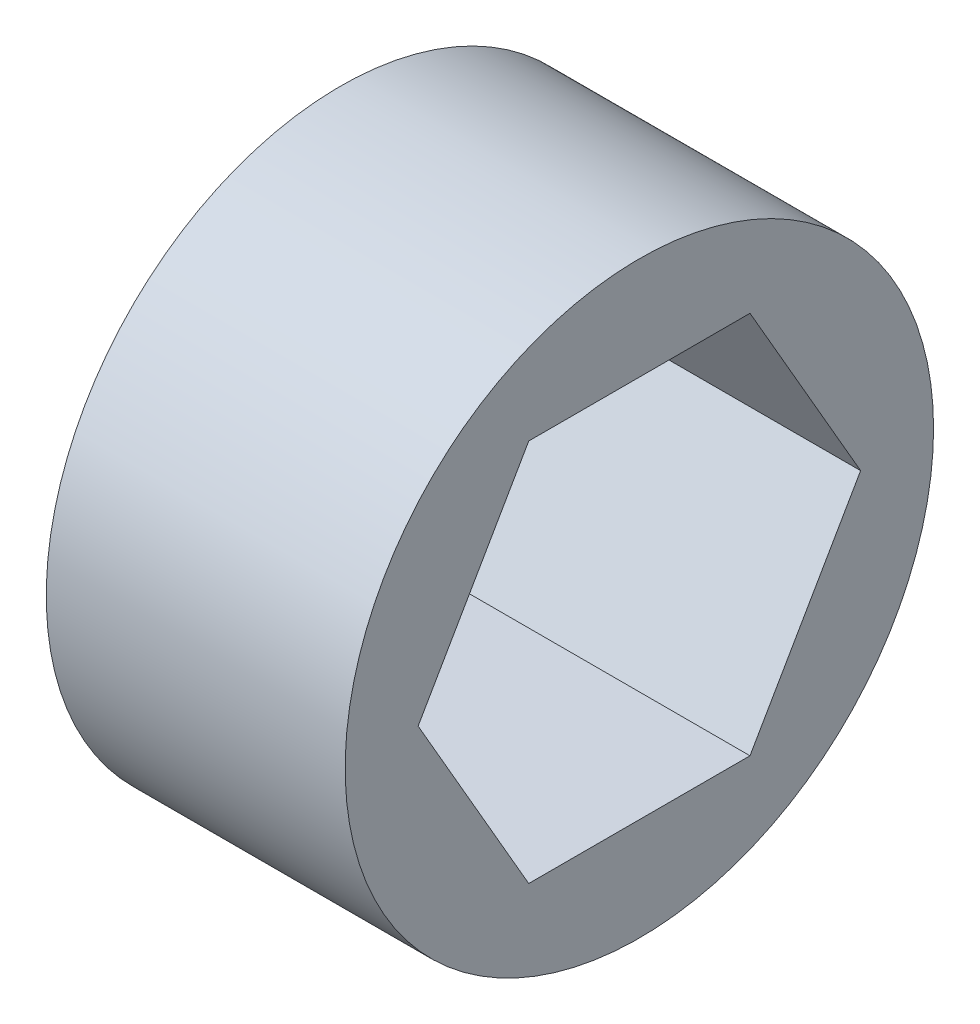
SolidWorks part; units mm, degrees
material "Delrin 2700 NC010, Low Viscosity Acetal Copolymer (SS)"
ref_plane "Front Plane" through (0, 0, 0) normal (0, 0, 1) x (1, 0, 0)
ref_plane "Top Plane" through (0, 0, 0) normal (0, 1, 0) x (1, 0, 0)
ref_plane "Right Plane" through (0, 0, 0) normal (1, 0, 0) x (0, 0, -1)
sketch "Sketch1" plane through (0, 0, 0) normal (1, 0, 0) x (0, 0, -1)
  line L1 (-3.6662, 6.35) -> (-7.3323, 0)
  line L2 (-7.3323, 0) -> (-3.6662, -6.35)
  line L3 (-3.6662, -6.35) -> (3.6662, -6.35)
  line L4 (3.6662, -6.35) -> (7.3323, 0)
  line L5 (7.3323, 0) -> (3.6662, 6.35)
  line L6 (3.6662, 6.35) -> (-3.6662, 6.35)
  circle A0 centre (0, 0) radius 9.75
  circle A1 centre (0, 0) radius 6.35 construction
  dimension "D1" = 19.5
  dimension "D2" = 12.7
extrude "Boss-Extrude1" add sketch "Sketch1" along normal blind 9.906
